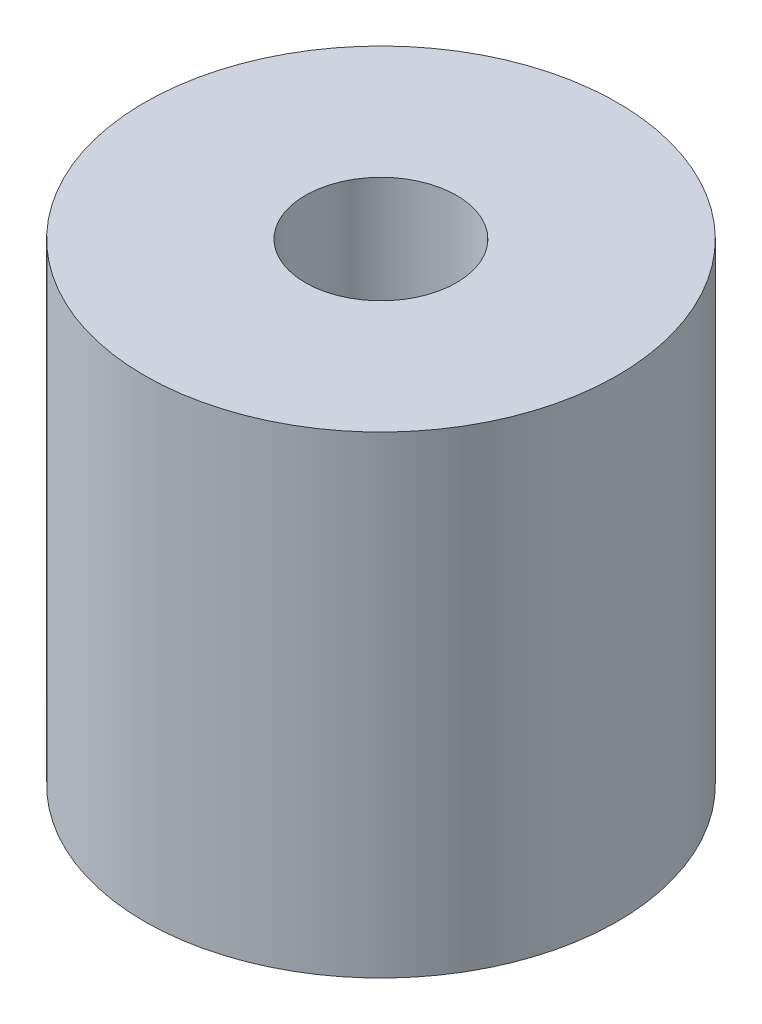
SolidWorks part; units mm, degrees
ref_plane "Front Plane" through (0, 0, 0) normal (0, 0, 1) x (1, 0, 0)
ref_plane "Top Plane" through (0, 0, 0) normal (0, 1, 0) x (1, 0, 0)
ref_plane "Right Plane" through (0, 0, 0) normal (1, 0, 0) x (0, 0, -1)
sketch "Sketch1" plane through (0, 0, 0) normal (0, 1, 0) x (1, 0, 0)
  circle A0 centre (0, 0) radius 1.6
  circle A1 centre (0, 0) radius 5
  dimension "D1" = 3.2
  dimension "D2" = 10
extrude "Boss-Extrude1" add sketch "Sketch1" along normal blind 10
